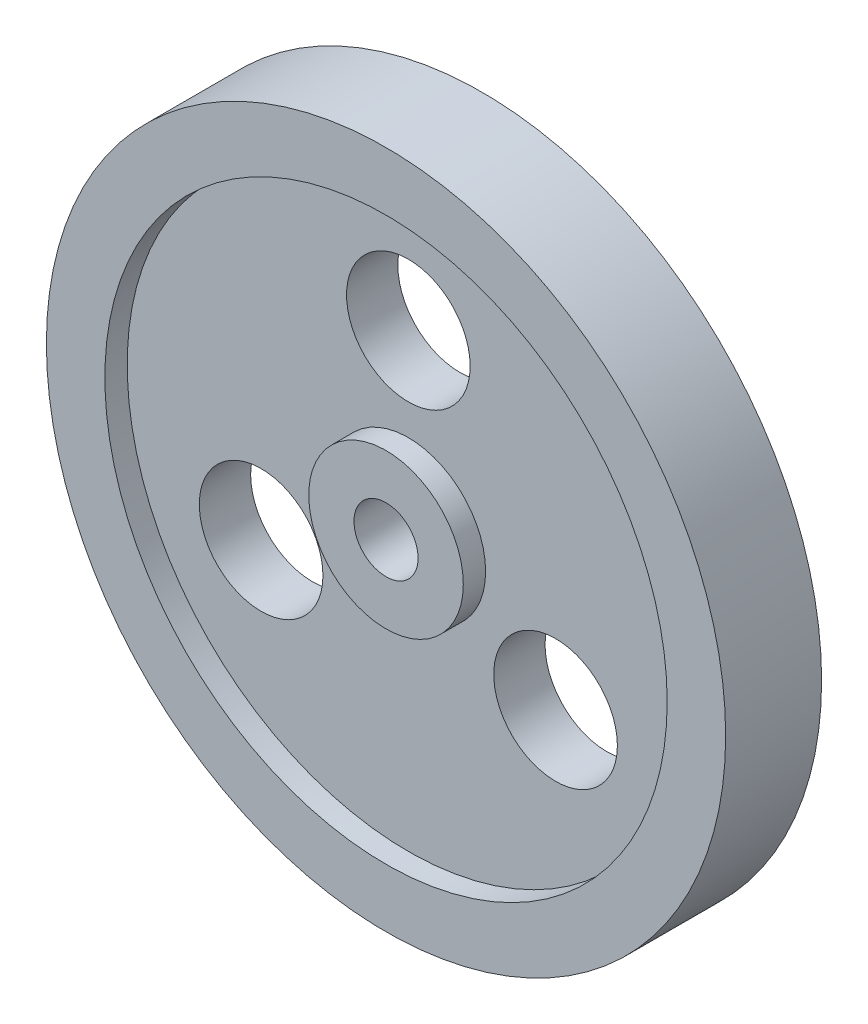
SolidWorks part; units mm, degrees
ref_plane "Front Plane" through (0, 0, 0) normal (0, 0, 1) x (1, 0, 0)
ref_plane "Top Plane" through (0, 0, 0) normal (0, 1, 0) x (1, 0, 0)
ref_plane "Right Plane" through (0, 0, 0) normal (1, 0, 0) x (0, 0, -1)
sketch "Sketch1" plane through (0, 0, 0) normal (0, 0, 1) x (1, 0, 0)
  circle A0 centre (0, 0) radius 19.781
  circle A1 centre (0, 0) radius 1.8669
  dimension "D1" = 39.5619
  dimension "D2" = 3.7338
extrude "Boss-Extrude1" add sketch "Sketch1" along normal mid plane 5.588
sketch "Sketch2" plane through (0, 0, 2.794) normal (0, 0, 1) x (1, 0, 0)
  circle A0 centre (0, 0) radius 16.375
  circle A1 centre (0, 0) radius 4.5
  dimension "D1" = 32.75
  dimension "D2" = 9
extrude "Cut-Extrude1" cut sketch "Sketch2" against normal blind 1.3
mirror "Mirror1" about plane through (0, 0, 0) normal (0, 0, 1) of "Cut-Extrude1"
sketch "Sketch3" plane through (0, 0, 1.494) normal (0, 0, 1) x (1, 0, 0)
  line L0 (0, 0) -> (0, 10.8598)
  circle A0 centre (0, 9.9) radius 3.6
  circle A1 centre (8.5737, -4.95) radius 3.6
  circle A2 centre (-8.5737, -4.95) radius 3.6
  point P9 (0, 0)
  dimension "D1" = 7.2
  dimension "D2" = 9.9
  dimension "D3" = 3
extrude "Cut-Extrude2" cut sketch "Sketch3" against normal through all
